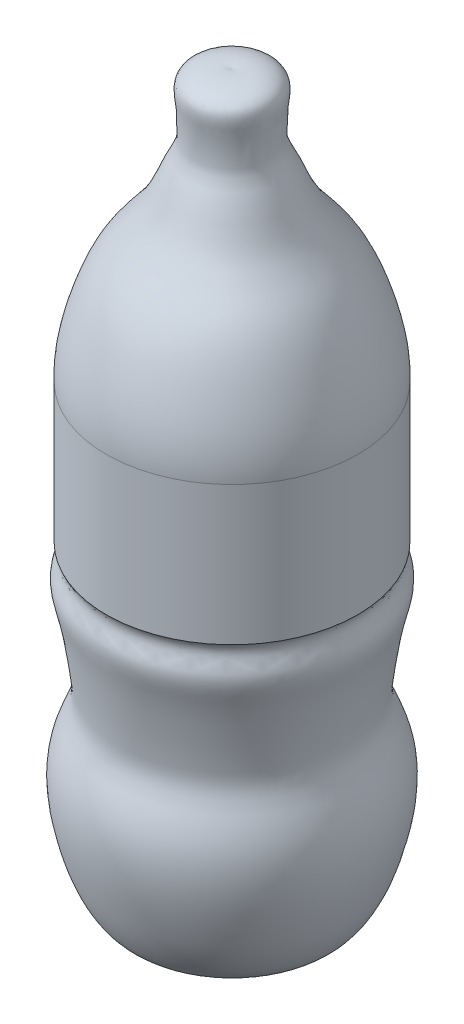
SolidWorks part; units mm, degrees
ref_plane "Alzado" through (0, 0, 0) normal (0, 0, 1) x (1, 0, 0)
ref_plane "Planta" through (0, 0, 0) normal (0, 1, 0) x (1, 0, 0)
ref_plane "Vista lateral" through (0, 0, 0) normal (1, 0, 0) x (0, 0, -1)
sketch "Croquis1" plane through (0, 0, 0) normal (0, 0, 1) x (1, 0, 0)
  line L0 (352.5608, 750.2743) -> (1352.9265, 750.2743) construction
  line L1 (249.7506, 0) -> (249.7506, 300)
  dimension "D1" = 300
sketch "Croquis3" plane through (0, 0, 0) normal (0, 0, 1) x (1, 0, 0)
  line L0 (301.0288, 132.7614) -> (301.0288, 189.3299)
  line L1 (249.7506, 4.0476) -> (249.7506, 300) construction
  line L2 (249.7506, 0) -> (249.7506, 300) construction
  line L3 (249.7506, 0) -> (249.7506, 300)
  spline S0 degree 3 poles (249.7506, 0) (258.7682, -7.7291) (260.413, 11.5213) (271.532, 5.4923) (277.3917, 4.1606) (287.1289, 3.4298) (294.805, 13.9796) (301.2936, 32.2414) (305.0635, 52.7205) (299.5232, 69.0155) (295.1069, 78.1649) (297.1613, 93.1529) (299.0728, 107.3653) (303.7284, 122.6711) (298.4562, 129.0881) (301.0288, 132.7614) knots 0 0 0 0 0.111971 0.132074 0.195427 0.221308 0.292867 0.386805 0.571066 0.625386 0.682682 0.74155 0.877711 0.939291 1 1 1 1
  spline S1 degree 3 poles (301.0288, 189.3299) (301.4149, 198.5203) (297.7336, 214.6986) (289.2659, 235.8853) (275.304, 249.8859) (270.7812, 264.239) (265.0179, 274.2329) (265.7847, 279.9208) (265.7768, 283.3391) (265.6197, 287.8993) (269.4531, 299.9595) (253.6194, 300.9095) (249.7506, 300) knots 0 0 0 0 0.208384 0.372389 0.512163 0.645579 0.712486 0.765289 0.771501 0.790138 0.870896 1 1 1 1
revolve "Revolución1" add sketch "Croquis3" angle 360 about L1
